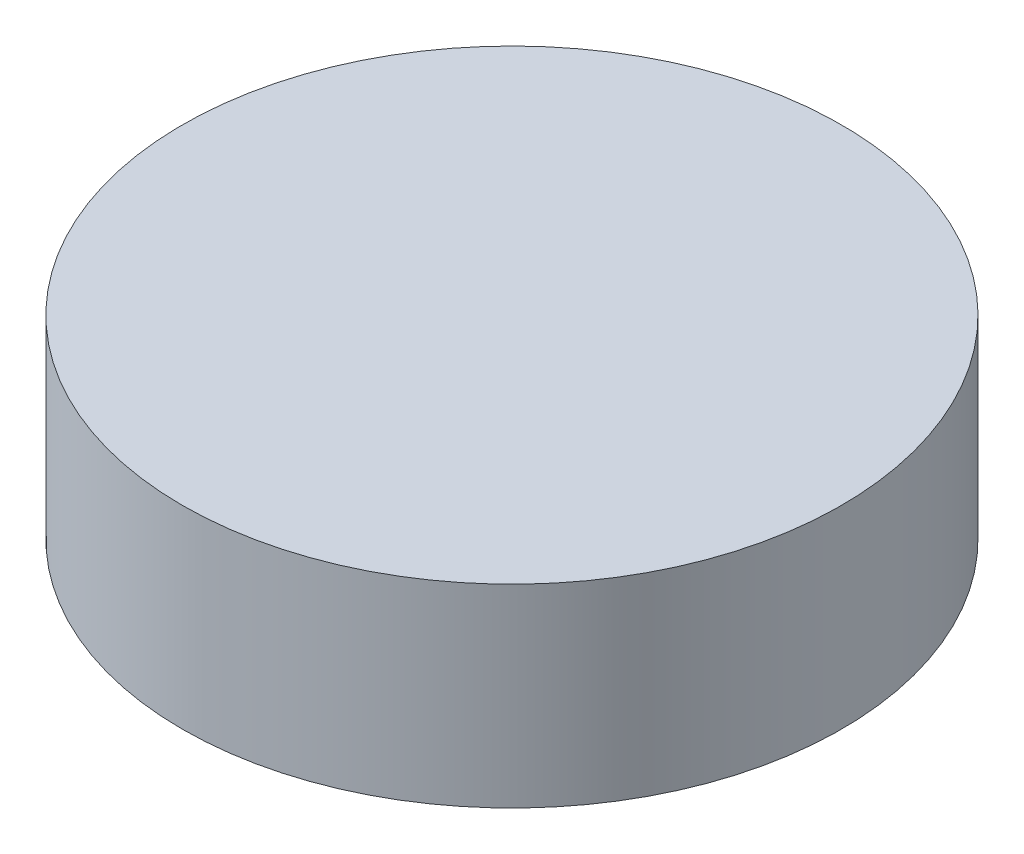
SolidWorks part; units mm, degrees
ref_plane "Front Plane" through (0, 0, 0) normal (0, 0, 1) x (1, 0, 0)
ref_plane "Top Plane" through (0, 0, 0) normal (0, 1, 0) x (1, 0, 0)
ref_plane "Right Plane" through (0, 0, 0) normal (1, 0, 0) x (0, 0, -1)
sketch "Sketch1" plane through (0, 0, 0) normal (0, 1, 0) x (1, 0, 0)
  circle A0 centre (4.9997, -4.9619) radius 10.795
  dimension "D1" = 21.59
extrude "Boss-Extrude1" add sketch "Sketch1" along normal blind 6.35
